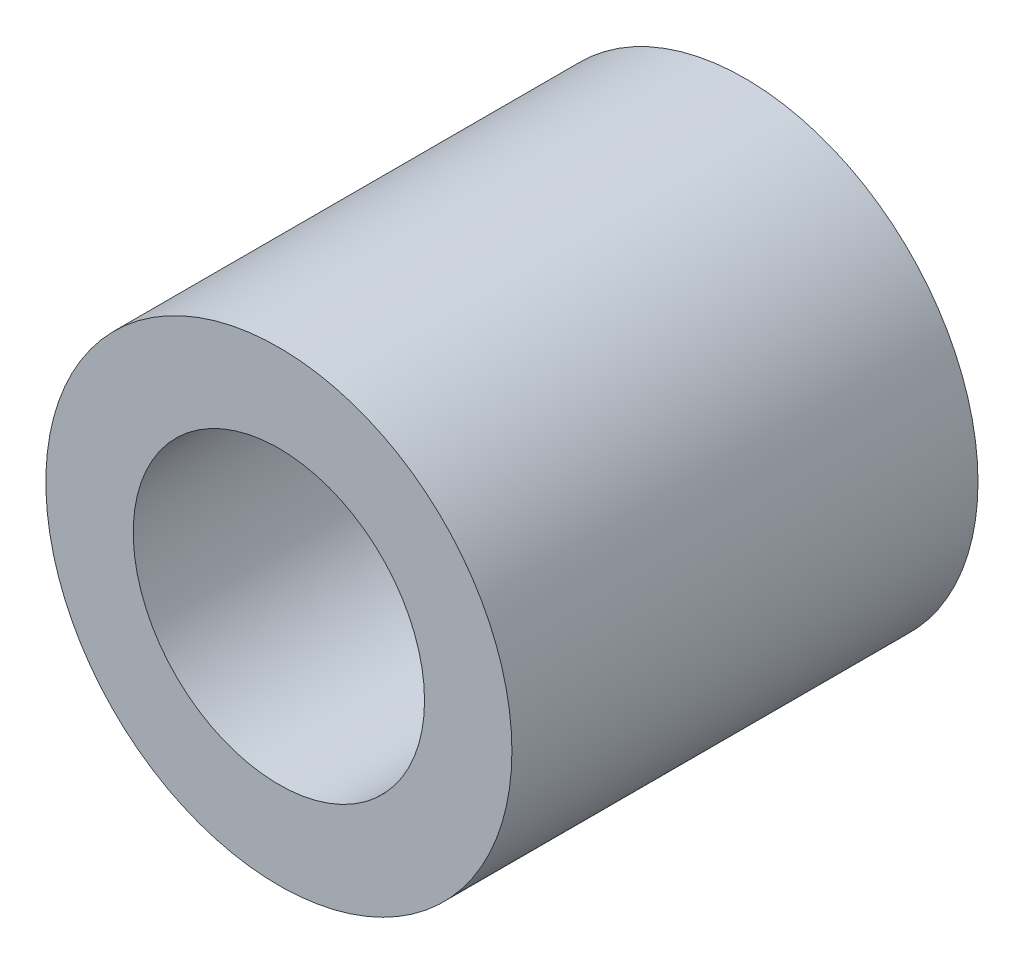
SolidWorks part; units mm, degrees
ref_plane "Front Plane" through (0, 0, 0) normal (0, 0, 1) x (1, 0, 0)
ref_plane "Top Plane" through (0, 0, 0) normal (0, 1, 0) x (1, 0, 0)
ref_plane "Right Plane" through (0, 0, 0) normal (1, 0, 0) x (0, 0, -1)
sketch "Sketch1" plane through (0, 0, 0) normal (0, 0, 1) x (1, 0, 0)
  line L0 (0, -23) -> (0, -42243.2323) construction
  line L1 (-1, -9.9593) -> (-1, -18.2087)
  line L2 (11.5, 0) -> (9.125, 4.1136)
  line L3 (5.75, 9.9593) -> (1, 9.9593)
  line L4 (-5.75, 9.9593) -> (-8.125, 5.8457)
  line L5 (-11.5, 0) -> (-9.125, -4.1136)
  line L6 (-5.75, -9.9593) -> (-1, -9.9593)
  line L7 (5.75, -9.9593) -> (8.125, -5.8457)
  line L8 (1, -9.9593) -> (1, -18.2087)
  line L9 (-9.125, -4.1136) -> (-16.2692, -8.2383)
  line L10 (-8.125, -5.8457) -> (-15.2692, -9.9704)
  line L11 (-8.125, 5.8457) -> (-15.2692, 9.9704)
  line L12 (-9.125, 4.1136) -> (-16.2692, 8.2383)
  line L13 (1, 9.9593) -> (1, 18.2087)
  line L14 (-1, 9.9593) -> (-1, 18.2087)
  line L15 (9.125, 4.1136) -> (16.2692, 8.2383)
  line L16 (8.125, 5.8457) -> (15.2692, 9.9704)
  line L17 (8.125, -5.8457) -> (15.2692, -9.9704)
  line L18 (9.125, -4.1136) -> (16.2692, -8.2383)
  line L19 (-8.125, -5.8457) -> (-5.75, -9.9593)
  line L20 (1, -9.9593) -> (5.75, -9.9593)
  line L21 (9.125, -4.1136) -> (11.5, 0)
  line L22 (8.125, 5.8457) -> (5.75, 9.9593)
  line L23 (-1, 9.9593) -> (-5.75, 9.9593)
  line L24 (-9.125, 4.1136) -> (-11.5, 0)
  arc A0 (-1, -18.2087) -> (-2.4953, -20.3476) centre (0, -20.5) ccw
  arc A1 (-16.3738, -12.3348) -> (-2.4953, -20.3476) centre (0, 0) ccw
  circle A2 centre (0, 0) radius 23
  arc A3 (-16.2692, -8.2383) -> (-18.8692, -8.0127) centre (-17.7535, -10.25) ccw
  arc A4 (-15.2692, 9.9704) -> (-16.3738, 12.3348) centre (-17.7535, 10.25) ccw
  arc A5 (1, 18.2087) -> (2.4953, 20.3476) centre (0, 20.5) ccw
  arc A6 (16.2692, 8.2383) -> (18.8692, 8.0127) centre (17.7535, 10.25) ccw
  arc A7 (15.2692, -9.9704) -> (16.3738, -12.3348) centre (17.7535, -10.25) ccw
  arc A8 (2.4953, -20.3476) -> (16.3738, -12.3348) centre (0, 0) ccw
  arc A9 (18.8692, -8.0127) -> (18.8692, 8.0127) centre (0, 0) ccw
  arc A10 (16.3738, 12.3348) -> (2.4953, 20.3476) centre (0, 0) ccw
  arc A11 (-2.4953, 20.3476) -> (-16.3738, 12.3348) centre (0, 0) ccw
  arc A12 (-18.8692, 8.0127) -> (-18.8692, -8.0127) centre (0, 0) ccw
  arc A13 (-16.3738, -12.3348) -> (-15.2692, -9.9704) centre (-17.7535, -10.25) ccw
  arc A14 (2.4953, -20.3476) -> (1, -18.2087) centre (0, -20.5) ccw
  arc A15 (18.8692, -8.0127) -> (16.2692, -8.2383) centre (17.7535, -10.25) ccw
  arc A16 (16.3738, 12.3348) -> (15.2692, 9.9704) centre (17.7535, 10.25) ccw
  arc A17 (-2.4953, 20.3476) -> (-1, 18.2087) centre (0, 20.5) ccw
  arc A18 (-18.8692, 8.0127) -> (-16.2692, 8.2383) centre (-17.7535, 10.25) ccw
  circle A19 centre (0, 0) radius 5
  circle A20 centre (0, 0) radius 8
  point P52 (0, 0)
  point P56 (0, 0)
  dimension "D1" = 41
  dimension "D2" = 46
  dimension "D4" = 5
  dimension "D7" = 2.5
  dimension "D8" = 10
  dimension "D9" = 16
  dimension "D3" = 23
  dimension "D5" = 1
  dimension "D6" = 6
extrude "Boss-Extrude1" add sketch "Sketch1" along normal mid plane 16 contours A20 A19
